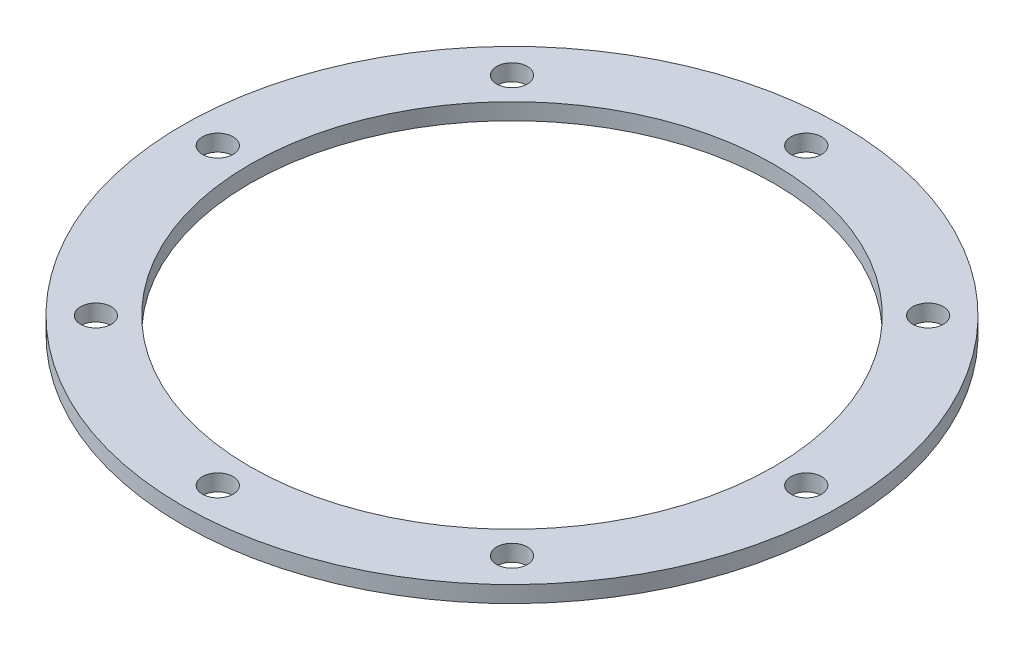
SolidWorks part; units mm, degrees
material "PLA"
ref_plane "Front Plane" through (0, 0, 0) normal (0, 0, 1) x (1, 0, 0)
ref_plane "Top Plane" through (0, 0, 0) normal (0, 1, 0) x (1, 0, 0)
ref_plane "Right Plane" through (0, 0, 0) normal (1, 0, 0) x (0, 0, -1)
sketch "Sketch1" plane through (0, 0, 0) normal (0, 1, 0) x (1, 0, 0)
  circle A0 centre (0, 0) radius 28
  circle A1 centre (0, 0) radius 22.25
  dimension "D1" = 56
  dimension "D2" = 44.5
extrude "Boss-Extrude1" add sketch "Sketch1" along normal blind 1.4
sketch "Sketch2" plane through (0, 1.4, 0) normal (0, 1, 0) x (1, 0, 0)
  line L0 (0, -1000) -> (0, 49000) construction
hole_wizard "M2 Clearance Hole1" positions "Sketch3" profile "Sketch4" hole size "M2" standard "ANSI Metric"
sketch "Sketch3" plane through (0, 1.4, 0) normal (0, 1, 0) x (1, 0, 0)
  line L0 (0, -201000) -> (0, 249000) construction
  point P0 (0, 25)
  dimension "D1" = 25
sketch "Sketch4" plane through (0, 1.4, -25) normal (1, 0, 0) x (0, 0, 1)
  line L0 (0, 0) -> (0, 17.7991)
  line L1 (0, 17.7991) -> (1.3, 17.018)
  line L2 (1.3, 17.018) -> (1.3, 0)
  line L5 (1.3, 0) -> (0, 0)
  line L10 (0, 17.7991) -> (-1.3, 17.018) construction
  line L11 (0, -6.35) -> (0, 107.95) construction
  dimension "Hole Dia." = 2.6
  dimension "Hole Depth" = 17.018
  dimension "Drill Angle" = 118
pattern_circular "CirPattern1" count 8 every 45 about axis through (0, 0, 0) along (0, 1, 0) of "M2 Clearance Hole1"
move or copy body "Body-Move/Copy1" [suppressed]
